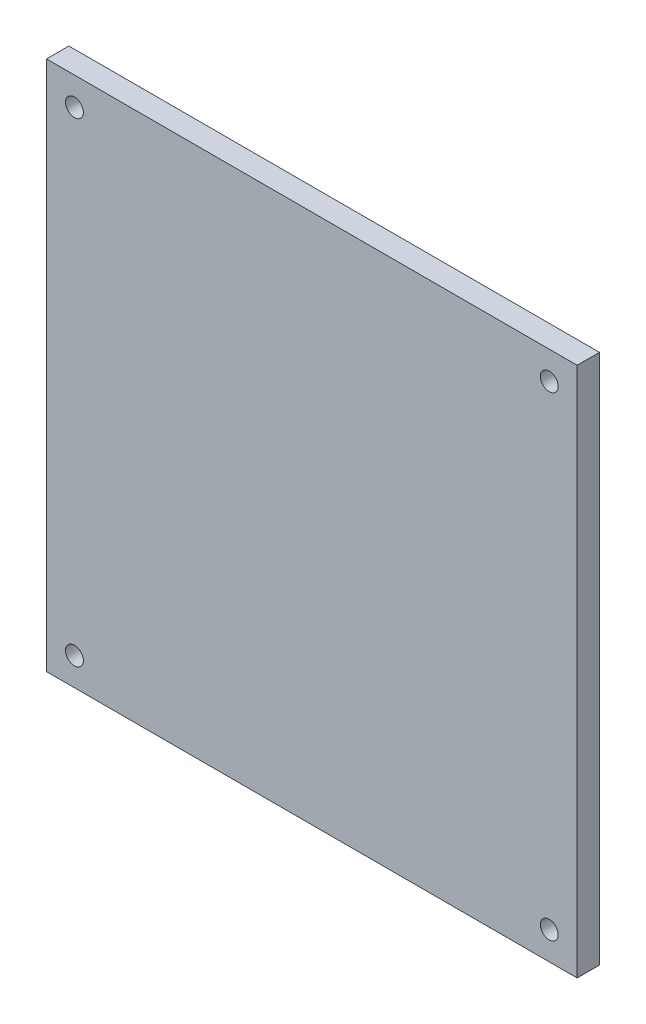
SolidWorks part; units mm, degrees
material "6061 合金"
ref_plane "Front Plane" through (0, 0, 0) normal (0, 0, 1) x (1, 0, 0)
ref_plane "Top Plane" through (0, 0, 0) normal (0, 1, 0) x (1, 0, 0)
ref_plane "Right Plane" through (0, 0, 0) normal (1, 0, 0) x (0, 0, -1)
sketch "草图1" plane through (0, 0, 0) normal (0, 0, 1) x (1, 0, 0)
  line L1 (47.5, 47.5) -> (0, 47.5)
  line L2 (47.5, 47.5) -> (47.5, 0)
  line L3 (47.5, 0) -> (0, 0)
  line L4 (0, 47.5) -> (0, 0)
extrude "凸台-拉伸1" add sketch "草图1" along normal blind 2
sketch "草图2" plane through (0, 0, 2) normal (0, 0, 1) x (1, 0, 0)
  circle A0 centre (2.5, 2.5) radius 0.8
  circle A1 centre (2.5, 45) radius 0.8
  circle A2 centre (45, 45) radius 0.8
  circle A3 centre (45, 2.5) radius 0.8
  point P10 (23.75, 23.75)
  dimension "D1" = 4
extrude "切除-拉伸1" cut sketch "草图2" against normal blind 2
